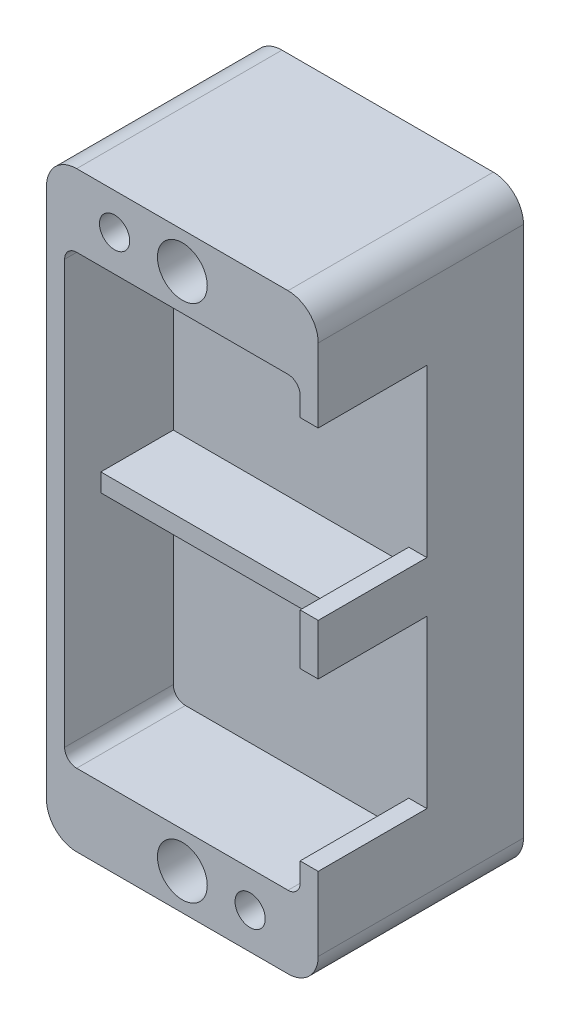
SolidWorks part; units mm, degrees
ref_plane "Alzado" through (0, 0, 0) normal (1, 0, 0) x (0, 1, 0)
ref_plane "Planta" through (0, 0, 0) normal (0, 0, 1) x (0, 1, 0)
ref_plane "Vista lateral" through (0, 0, 0) normal (0, 1, 0) x (-1, 0, 0)
sketch "Croquis1" plane through (0, 0, 0) normal (0, 0, 1) x (0, 1, 0)
  line L1 (-49, -22.5) -> (49, -22.5)
  line L2 (-49, -22.5) -> (-49, 22.5)
  line L3 (-49, 22.5) -> (49, 22.5)
  line L4 (49, -22.5) -> (49, 22.5)
  line L5 (-49, -22.5) -> (49, 22.5) construction
  line L6 (-49, 22.5) -> (49, -22.5) construction
  point P0 (0, 0)
  dimension "D1" = 98
  dimension "D2" = 45
extrude "Saliente-Extruir1" add sketch "Croquis1" along normal blind 34
fillet "Redondeo1" radius 5 4 edges at (-22.5, -49, 17) (-22.5, 49, 17) (22.5, 49, 17) (22.5, -49, 17)
sketch "Croquis2" plane through (0, 0, 34) normal (0, 0, 1) x (1, 0, 0)
  line L0 (0, 43) -> (0, -43) construction
  line L1 (-11.225, 43) -> (0, 43) construction
  line L3 (17.5, 49) -> (-17.5, 49) construction
  circle A0 centre (0, 43) radius 4.125
  circle A1 centre (0, -43) radius 4.125
  circle A2 centre (-11.225, 43) radius 2.5
  circle A3 centre (11.225, -43) radius 2.5
  dimension "D2" = 8.25
  dimension "D3" = 8.25
  dimension "D4" = 5
  dimension "D5" = 5
  dimension "D6" = 4.6
  dimension "D7" = 4.6
  dimension "D1" = 6
extrude "Cortar-Extruir1" cut sketch "Croquis2" against normal blind 8
sketch "Croquis3" plane through (0, 0, 34) normal (0, 0, 1) x (1, 0, 0)
  line L0 (32.9237, 0) -> (-36.7531, 0) construction
  line L2 (-19.5, -35) -> (-19.5, 35)
  line L3 (-17.5, 37) -> (17.5, 37)
  line L4 (19.5, -4.2073) -> (19.5, 4.2073)
  line L5 (0, 0) -> (19.5, 37) construction
  line L6 (-19.5, 37) -> (0, 0) construction
  line L7 (22.5, -44) -> (22.5, 44) construction
  line L8 (19.5, 31.7927) -> (22.5, 31.7927)
  line L10 (19.5, 4.2073) -> (22.5, 4.2073)
  line L11 (22.5, 31.7927) -> (22.5, 4.2073)
  line L12 (19.5, 18) -> (22.5, 4.2073) construction
  line L13 (19.5, 18) -> (22.5, 31.7927) construction
  line L14 (-22.5, 44) -> (-22.5, -44) construction
  line L15 (19.5, 31.7927) -> (19.5, 35)
  line L16 (19.5, -18) -> (22.5, -31.7927) construction
  line L17 (19.5, -18) -> (22.5, -4.2073) construction
  line L18 (-19.5, -37) -> (0, 0) construction
  line L19 (0, 0) -> (19.5, -37) construction
  line L20 (19.5, -31.7927) -> (19.5, -35)
  line L21 (22.5, -31.7927) -> (22.5, -4.2073)
  line L22 (19.5, -4.2073) -> (22.5, -4.2073)
  line L23 (19.5, -31.7927) -> (22.5, -31.7927)
  line L24 (-17.5, -37) -> (17.5, -37)
  line L27 (17.5, 49) -> (-17.5, 49) construction
  arc A0 (-19.5, 35) -> (-17.5, 37) centre (-17.5, 35) cw
  arc A1 (17.5, 37) -> (19.5, 35) centre (17.5, 35) cw
  arc A2 (17.5, -37) -> (19.5, -35) centre (17.5, -35) ccw
  arc A3 (-19.5, -35) -> (-17.5, -37) centre (-17.5, -35) ccw
  point P0 (0, 0)
  point P4 (19.5, -18)
  point P8 (-19.5, 0)
  point P15 (19.5, 18)
  point P40 (19.5, 0)
  dimension "D1" = 2
  dimension "D2" = 3
  dimension "D3" = 3
  dimension "D4" = 12
extrude "Cortar-Extruir2" cut sketch "Croquis3" against normal blind 18
sketch "Croquis4" plane through (0, 0, 16) normal (0, 0, 1) x (1, 0, 0)
  line L0 (19.5, -4.2073) -> (19.5, 4.2073) construction
  line L1 (-19.5, -1.5) -> (19.5, -1.5)
  line L2 (-19.5, -1.5) -> (-19.5, 1.5)
  line L3 (-19.5, 1.5) -> (19.5, 1.5)
  line L4 (19.5, -1.5) -> (19.5, 1.5)
  line L5 (-19.5, -1.5) -> (19.5, 1.5) construction
  line L6 (-19.5, 1.5) -> (19.5, -1.5) construction
  point P0 (0, 0)
  dimension "D1" = 3
extrude "Saliente-Extruir2" add sketch "Croquis4" along normal blind 12
sketch "Croquis5" plane through (-22.5, 0, 0) normal (-1, 0, 0) x (0, -1, 0)
  line L0 (0, 43.1669) -> (0, -9.1373) construction
  line L1 (-31.7927, 34) -> (-35, 34) construction
  line L2 (-35, 34) -> (-35, 16) construction
  line L3 (-35, 16) -> (-31.7927, 16) construction
  line L4 (-31.7927, 16) -> (-31.7927, 34) construction
  line L5 (-1.5, 16) -> (-1.5, 28) construction
  line L6 (-1.5, 28) -> (1.5, 28) construction
  line L7 (-2.8536, 8) -> (-12.7461, 8) construction
  line L10 (4.2073, 34) -> (-4.2073, 34) construction
  line L11 (-4.2073, 34) -> (-4.2073, 16) construction
  line L12 (-4.2073, 16) -> (-1.5, 16) construction
  line L13 (-31.7927, 34) -> (-35, 34) construction
  line L14 (-35, 34) -> (-35, 16) construction
  line L15 (-35, 16) -> (-31.7927, 16) construction
  line L16 (-31.7927, 16) -> (-31.7927, 34) construction
  line L17 (-1.5, 16) -> (-1.5, 28) construction
  line L18 (-1.5, 28) -> (0, 28) construction
  line L22 (0, 34) -> (-4.2073, 34) construction
  line L23 (-4.2073, 34) -> (-4.2073, 16) construction
  line L24 (-4.2073, 16) -> (-1.5, 16) construction
  line L25 (-44, 0) -> (44, 0) construction
  line L26 (-2.8536, 16) -> (-2.8536, 0) construction
  circle A0 centre (-7.7496, 8) radius 3.5423
  circle A1 centre (-18, 8) radius 3.5423
  circle A2 centre (-28.2504, 8) radius 3.5423
  circle A3 centre (28.2504, 8) radius 3.5423
  circle A4 centre (18, 8) radius 3.5423
  circle A5 centre (7.7496, 8) radius 3.5423
  dimension "D1" = 3
extrude "Cortar-Extruir3" cut sketch "Croquis5" against normal blind 21
